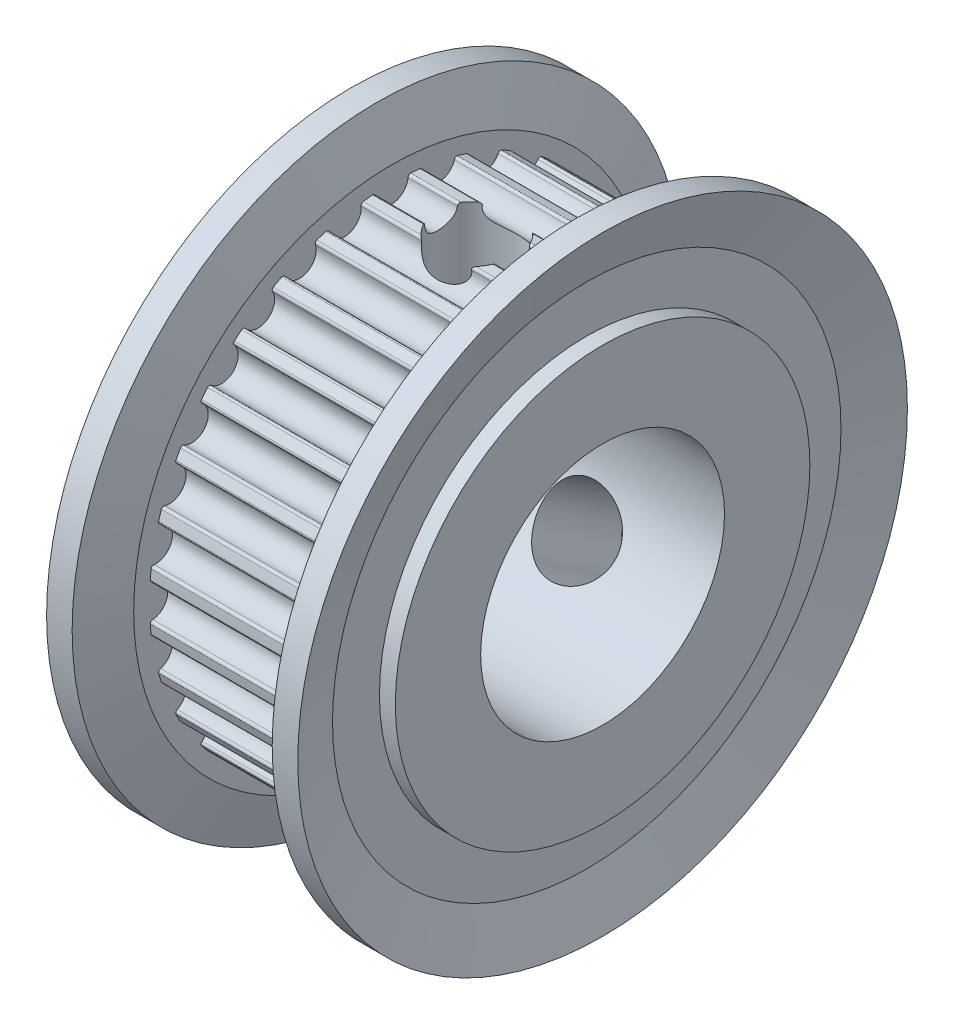
SolidWorks part; units mm, degrees
ref_plane "Front Plane" through (0, 0, 0) normal (0, 0, 1) x (1, 0, 0)
ref_plane "Top Plane" through (0, 0, 0) normal (0, 1, 0) x (1, 0, 0)
ref_plane "Right Plane" through (0, 0, 0) normal (1, 0, 0) x (0, 0, -1)
ref_plane "Plane1" through (0, 0, 0) normal (0, 0, 1) x (1, 0, 0)
sketch "Sketch1" plane through (0, 0, 0) normal (0, 0, 1) x (1, 0, 0)
  line L0 (-5.15, 0) -> (-5.15, 8.5)
  line L1 (-5.15, 8.5) -> (-3.5, 8.5)
  line L2 (-3.5, 8.5) -> (-3.5, 9.93)
  line L3 (-3.5, 9.93) -> (3.5, 9.93)
  line L4 (3.5, 9.93) -> (3.5, 8.5)
  line L5 (3.5, 8.5) -> (5.15, 8.5)
  line L6 (5.15, 8.5) -> (5.15, 0)
  line L7 (5.15, 0) -> (-5.15, 0)
  line L8 (5.15, 0) -> (-5.15, 0) construction
revolve "Revolve1" add sketch "Sketch1" angle 360 about L8
ref_plane "Plane2" through (0, 0, 0) normal (1, 0, 0) x (0, 0, -1)
sketch "Sketch2" plane through (0, 0, 0) normal (1, 0, 0) x (0, 0, -1)
  line L0 (-0.9509, 10.1405) -> (-0.9273, 9.8885)
  line L1 (-0.9273, 9.8885) -> (-0.793, 9.8993)
  line L2 (0.793, 9.8993) -> (0.9273, 9.8885)
  line L3 (0.9273, 9.8885) -> (0.9509, 10.1405)
  arc A0 (-0.793, 9.8993) -> (-0.6724, 9.7974) centre (-0.784, 9.7876) cw
  arc A1 (-0.6724, 9.7974) -> (0.6724, 9.7974) centre (0, 9.856) ccw
  arc A2 (0.6724, 9.7974) -> (0.793, 9.8993) centre (0.784, 9.7876) cw
  arc A3 (0.9509, 10.1405) -> (-0.9509, 10.1405) centre (0, 0) ccw
extrude "Cut-Extrude1" cut sketch "Sketch2" against normal blind 3.5 and the other way blind 3.5
ref_plane "Plane3" through (0, 0, 0) normal (1, 0, 0) x (0, 0, -1)
sketch "Sketch3" plane through (0, 0, 0) normal (1, 0, 0) x (0, 0, -1)
  line L0 (-2.911, 9.7602) -> (-2.8386, 9.5176)
  line L1 (-2.8386, 9.5176) -> (-2.709, 9.5544)
  line L2 (-1.1535, 9.8638) -> (-1.0197, 9.8794)
  line L3 (-1.0197, 9.8794) -> (-1.0457, 10.1312)
  arc A0 (-2.709, 9.5544) -> (-2.5709, 9.4779) centre (-2.6784, 9.4466) cw
  arc A1 (-2.5709, 9.4779) -> (-1.2518, 9.7403) centre (-1.9228, 9.6666) ccw
  arc A2 (-1.2518, 9.7403) -> (-1.1535, 9.8638) centre (-1.1405, 9.7525) cw
  arc A3 (-1.0457, 10.1312) -> (-2.911, 9.7602) centre (0, 0) ccw
extrude "Cut-Extrude2" cut sketch "Sketch3" against normal blind 3.5 and the other way blind 3.5
ref_plane "Plane4" through (0, 0, 0) normal (1, 0, 0) x (0, 0, -1)
sketch "Sketch4" plane through (0, 0, 0) normal (1, 0, 0) x (0, 0, -1)
  line L0 (-4.7591, 9.0047) -> (-4.6409, 8.781)
  line L1 (-4.6409, 8.781) -> (-4.5209, 8.8423)
  line L2 (-3.0557, 9.4492) -> (-2.9275, 9.4907)
  line L3 (-2.9275, 9.4907) -> (-3.0021, 9.7325)
  arc A0 (-4.5209, 8.8423) -> (-4.3706, 8.7943) centre (-4.4699, 8.7426) cw
  arc A1 (-4.3706, 8.7943) -> (-3.128, 9.3089) centre (-3.7717, 9.1058) ccw
  arc A2 (-3.128, 9.3089) -> (-3.0557, 9.4492) centre (-3.0212, 9.3426) cw
  arc A3 (-3.0021, 9.7325) -> (-4.7591, 9.0047) centre (0, 0) ccw
extrude "Cut-Extrude3" cut sketch "Sketch4" against normal blind 3.5 and the other way blind 3.5
ref_plane "Plane5" through (0, 0, 0) normal (1, 0, 0) x (0, 0, -1)
sketch "Sketch5" plane through (0, 0, 0) normal (1, 0, 0) x (0, 0, -1)
  line L0 (-6.4244, 7.9032) -> (-6.2648, 7.7068)
  line L1 (-6.2648, 7.7068) -> (-6.1591, 7.7904)
  line L2 (-4.8404, 8.6715) -> (-4.7228, 8.7372)
  line L3 (-4.7228, 8.7372) -> (-4.8431, 8.9598)
  arc A0 (-6.1591, 7.7904) -> (-6.0023, 7.7726) centre (-6.0896, 7.7026) cw
  arc A1 (-6.0023, 7.7726) -> (-4.884, 8.5198) centre (-5.4757, 8.195) ccw
  arc A2 (-4.884, 8.5198) -> (-4.8404, 8.6715) centre (-4.7858, 8.5737) cw
  arc A3 (-4.8431, 8.9598) -> (-6.4244, 7.9032) centre (0, 0) ccw
extrude "Cut-Extrude4" cut sketch "Sketch5" against normal blind 3.5 and the other way blind 3.5
ref_plane "Plane6" through (0, 0, 0) normal (1, 0, 0) x (0, 0, -1)
sketch "Sketch6" plane through (0, 0, 0) normal (1, 0, 0) x (0, 0, -1)
  line L0 (-7.8428, 6.498) -> (-7.6479, 6.3366)
  line L1 (-7.6479, 6.3366) -> (-7.5606, 6.4391)
  line L2 (-6.4391, 7.5606) -> (-6.3366, 7.6479)
  line L3 (-6.3366, 7.6479) -> (-6.498, 7.8428)
  arc A0 (-7.5606, 6.4391) -> (-7.4033, 6.4523) centre (-7.4753, 6.3665) cw
  arc A1 (-7.4033, 6.4523) -> (-6.4523, 7.4033) centre (-6.9692, 6.9692) ccw
  arc A2 (-6.4523, 7.4033) -> (-6.4391, 7.5606) centre (-6.3665, 7.4753) cw
  arc A3 (-6.498, 7.8428) -> (-7.8428, 6.498) centre (0, 0) ccw
extrude "Cut-Extrude5" cut sketch "Sketch6" against normal blind 3.5 and the other way blind 3.5
ref_plane "Plane7" through (0, 0, 0) normal (1, 0, 0) x (0, 0, -1)
sketch "Sketch7" plane through (0, 0, 0) normal (1, 0, 0) x (0, 0, -1)
  line L0 (-8.9598, 4.8431) -> (-8.7372, 4.7228)
  line L1 (-8.7372, 4.7228) -> (-8.6715, 4.8404)
  line L2 (-7.7904, 6.1591) -> (-7.7068, 6.2648)
  line L3 (-7.7068, 6.2648) -> (-7.9032, 6.4244)
  arc A0 (-8.6715, 4.8404) -> (-8.5198, 4.884) centre (-8.5737, 4.7858) cw
  arc A1 (-8.5198, 4.884) -> (-7.7726, 6.0023) centre (-8.195, 5.4757) ccw
  arc A2 (-7.7726, 6.0023) -> (-7.7904, 6.1591) centre (-7.7026, 6.0896) cw
  arc A3 (-7.9032, 6.4244) -> (-8.9598, 4.8431) centre (0, 0) ccw
extrude "Cut-Extrude6" cut sketch "Sketch7" against normal blind 3.5 and the other way blind 3.5
ref_plane "Plane8" through (0, 0, 0) normal (1, 0, 0) x (0, 0, -1)
sketch "Sketch8" plane through (0, 0, 0) normal (1, 0, 0) x (0, 0, -1)
  line L0 (-9.7325, 3.0021) -> (-9.4907, 2.9275)
  line L1 (-9.4907, 2.9275) -> (-9.4492, 3.0557)
  line L2 (-8.8423, 4.5209) -> (-8.781, 4.6409)
  line L3 (-8.781, 4.6409) -> (-9.0047, 4.7591)
  arc A0 (-9.4492, 3.0557) -> (-9.3089, 3.128) centre (-9.3426, 3.0212) cw
  arc A1 (-9.3089, 3.128) -> (-8.7943, 4.3706) centre (-9.1058, 3.7717) ccw
  arc A2 (-8.7943, 4.3706) -> (-8.8423, 4.5209) centre (-8.7426, 4.4699) cw
  arc A3 (-9.0047, 4.7591) -> (-9.7325, 3.0021) centre (0, 0) ccw
extrude "Cut-Extrude7" cut sketch "Sketch8" against normal blind 3.5 and the other way blind 3.5
ref_plane "Plane9" through (0, 0, 0) normal (1, 0, 0) x (0, 0, -1)
sketch "Sketch9" plane through (0, 0, 0) normal (1, 0, 0) x (0, 0, -1)
  line L0 (-10.1312, 1.0457) -> (-9.8794, 1.0197)
  line L1 (-9.8794, 1.0197) -> (-9.8638, 1.1535)
  line L2 (-9.5544, 2.709) -> (-9.5176, 2.8386)
  line L3 (-9.5176, 2.8386) -> (-9.7602, 2.911)
  arc A0 (-9.8638, 1.1535) -> (-9.7403, 1.2518) centre (-9.7525, 1.1405) cw
  arc A1 (-9.7403, 1.2518) -> (-9.4779, 2.5709) centre (-9.6666, 1.9228) ccw
  arc A2 (-9.4779, 2.5709) -> (-9.5544, 2.709) centre (-9.4466, 2.6784) cw
  arc A3 (-9.7602, 2.911) -> (-10.1312, 1.0457) centre (0, 0) ccw
extrude "Cut-Extrude8" cut sketch "Sketch9" against normal blind 3.5 and the other way blind 3.5
ref_plane "Plane10" through (0, 0, 0) normal (1, 0, 0) x (0, 0, -1)
sketch "Sketch10" plane through (0, 0, 0) normal (1, 0, 0) x (0, 0, -1)
  line L0 (-10.1405, -0.9509) -> (-9.8885, -0.9273)
  line L1 (-9.8885, -0.9273) -> (-9.8993, -0.793)
  line L2 (-9.8993, 0.793) -> (-9.8885, 0.9273)
  line L3 (-9.8885, 0.9273) -> (-10.1405, 0.9509)
  arc A0 (-9.8993, -0.793) -> (-9.7974, -0.6724) centre (-9.7876, -0.784) cw
  arc A1 (-9.7974, -0.6724) -> (-9.7974, 0.6724) centre (-9.856, 0) ccw
  arc A2 (-9.7974, 0.6724) -> (-9.8993, 0.793) centre (-9.7876, 0.784) cw
  arc A3 (-10.1405, 0.9509) -> (-10.1405, -0.9509) centre (0, 0) ccw
extrude "Cut-Extrude9" cut sketch "Sketch10" against normal blind 3.5 and the other way blind 3.5
ref_plane "Plane11" through (0, 0, 0) normal (1, 0, 0) x (0, 0, -1)
sketch "Sketch11" plane through (0, 0, 0) normal (1, 0, 0) x (0, 0, -1)
  line L0 (-9.7602, -2.911) -> (-9.5176, -2.8386)
  line L1 (-9.5176, -2.8386) -> (-9.5544, -2.709)
  line L2 (-9.8638, -1.1535) -> (-9.8794, -1.0197)
  line L3 (-9.8794, -1.0197) -> (-10.1312, -1.0457)
  arc A0 (-9.5544, -2.709) -> (-9.4779, -2.5709) centre (-9.4466, -2.6784) cw
  arc A1 (-9.4779, -2.5709) -> (-9.7403, -1.2518) centre (-9.6666, -1.9228) ccw
  arc A2 (-9.7403, -1.2518) -> (-9.8638, -1.1535) centre (-9.7525, -1.1405) cw
  arc A3 (-10.1312, -1.0457) -> (-9.7602, -2.911) centre (0, 0) ccw
extrude "Cut-Extrude10" cut sketch "Sketch11" against normal blind 3.5 and the other way blind 3.5
ref_plane "Plane12" through (0, 0, 0) normal (1, 0, 0) x (0, 0, -1)
sketch "Sketch12" plane through (0, 0, 0) normal (1, 0, 0) x (0, 0, -1)
  line L0 (-9.0047, -4.7591) -> (-8.781, -4.6409)
  line L1 (-8.781, -4.6409) -> (-8.8423, -4.5209)
  line L2 (-9.4492, -3.0557) -> (-9.4907, -2.9275)
  line L3 (-9.4907, -2.9275) -> (-9.7325, -3.0021)
  arc A0 (-8.8423, -4.5209) -> (-8.7943, -4.3706) centre (-8.7426, -4.4699) cw
  arc A1 (-8.7943, -4.3706) -> (-9.3089, -3.128) centre (-9.1058, -3.7717) ccw
  arc A2 (-9.3089, -3.128) -> (-9.4492, -3.0557) centre (-9.3426, -3.0212) cw
  arc A3 (-9.7325, -3.0021) -> (-9.0047, -4.7591) centre (0, 0) ccw
extrude "Cut-Extrude11" cut sketch "Sketch12" against normal blind 3.5 and the other way blind 3.5
ref_plane "Plane13" through (0, 0, 0) normal (1, 0, 0) x (0, 0, -1)
sketch "Sketch13" plane through (0, 0, 0) normal (1, 0, 0) x (0, 0, -1)
  line L0 (-7.9032, -6.4244) -> (-7.7068, -6.2648)
  line L1 (-7.7068, -6.2648) -> (-7.7904, -6.1591)
  line L2 (-8.6715, -4.8404) -> (-8.7372, -4.7228)
  line L3 (-8.7372, -4.7228) -> (-8.9598, -4.8431)
  arc A0 (-7.7904, -6.1591) -> (-7.7726, -6.0023) centre (-7.7026, -6.0896) cw
  arc A1 (-7.7726, -6.0023) -> (-8.5198, -4.884) centre (-8.195, -5.4757) ccw
  arc A2 (-8.5198, -4.884) -> (-8.6715, -4.8404) centre (-8.5737, -4.7858) cw
  arc A3 (-8.9598, -4.8431) -> (-7.9032, -6.4244) centre (0, 0) ccw
extrude "Cut-Extrude12" cut sketch "Sketch13" against normal blind 3.5 and the other way blind 3.5
ref_plane "Plane14" through (0, 0, 0) normal (1, 0, 0) x (0, 0, -1)
sketch "Sketch14" plane through (0, 0, 0) normal (1, 0, 0) x (0, 0, -1)
  line L0 (-6.498, -7.8428) -> (-6.3366, -7.6479)
  line L1 (-6.3366, -7.6479) -> (-6.4391, -7.5606)
  line L2 (-7.5606, -6.4391) -> (-7.6479, -6.3366)
  line L3 (-7.6479, -6.3366) -> (-7.8428, -6.498)
  arc A0 (-6.4391, -7.5606) -> (-6.4523, -7.4033) centre (-6.3665, -7.4753) cw
  arc A1 (-6.4523, -7.4033) -> (-7.4033, -6.4523) centre (-6.9692, -6.9692) ccw
  arc A2 (-7.4033, -6.4523) -> (-7.5606, -6.4391) centre (-7.4753, -6.3665) cw
  arc A3 (-7.8428, -6.498) -> (-6.498, -7.8428) centre (0, 0) ccw
extrude "Cut-Extrude13" cut sketch "Sketch14" against normal blind 3.5 and the other way blind 3.5
ref_plane "Plane15" through (0, 0, 0) normal (1, 0, 0) x (0, 0, -1)
sketch "Sketch15" plane through (0, 0, 0) normal (1, 0, 0) x (0, 0, -1)
  line L0 (-4.8431, -8.9598) -> (-4.7228, -8.7372)
  line L1 (-4.7228, -8.7372) -> (-4.8404, -8.6715)
  line L2 (-6.1591, -7.7904) -> (-6.2648, -7.7068)
  line L3 (-6.2648, -7.7068) -> (-6.4244, -7.9032)
  arc A0 (-4.8404, -8.6715) -> (-4.884, -8.5198) centre (-4.7858, -8.5737) cw
  arc A1 (-4.884, -8.5198) -> (-6.0023, -7.7726) centre (-5.4757, -8.195) ccw
  arc A2 (-6.0023, -7.7726) -> (-6.1591, -7.7904) centre (-6.0896, -7.7026) cw
  arc A3 (-6.4244, -7.9032) -> (-4.8431, -8.9598) centre (0, 0) ccw
extrude "Cut-Extrude14" cut sketch "Sketch15" against normal blind 3.5 and the other way blind 3.5
ref_plane "Plane16" through (0, 0, 0) normal (1, 0, 0) x (0, 0, -1)
sketch "Sketch16" plane through (0, 0, 0) normal (1, 0, 0) x (0, 0, -1)
  line L0 (-3.0021, -9.7325) -> (-2.9275, -9.4907)
  line L1 (-2.9275, -9.4907) -> (-3.0557, -9.4492)
  line L2 (-4.5209, -8.8423) -> (-4.6409, -8.781)
  line L3 (-4.6409, -8.781) -> (-4.7591, -9.0047)
  arc A0 (-3.0557, -9.4492) -> (-3.128, -9.3089) centre (-3.0212, -9.3426) cw
  arc A1 (-3.128, -9.3089) -> (-4.3706, -8.7943) centre (-3.7717, -9.1058) ccw
  arc A2 (-4.3706, -8.7943) -> (-4.5209, -8.8423) centre (-4.4699, -8.7426) cw
  arc A3 (-4.7591, -9.0047) -> (-3.0021, -9.7325) centre (0, 0) ccw
extrude "Cut-Extrude15" cut sketch "Sketch16" against normal blind 3.5 and the other way blind 3.5
ref_plane "Plane17" through (0, 0, 0) normal (1, 0, 0) x (0, 0, -1)
sketch "Sketch17" plane through (0, 0, 0) normal (1, 0, 0) x (0, 0, -1)
  line L0 (-1.0457, -10.1312) -> (-1.0197, -9.8794)
  line L1 (-1.0197, -9.8794) -> (-1.1535, -9.8638)
  line L2 (-2.709, -9.5544) -> (-2.8386, -9.5176)
  line L3 (-2.8386, -9.5176) -> (-2.911, -9.7602)
  arc A0 (-1.1535, -9.8638) -> (-1.2518, -9.7403) centre (-1.1405, -9.7525) cw
  arc A1 (-1.2518, -9.7403) -> (-2.5709, -9.4779) centre (-1.9228, -9.6666) ccw
  arc A2 (-2.5709, -9.4779) -> (-2.709, -9.5544) centre (-2.6784, -9.4466) cw
  arc A3 (-2.911, -9.7602) -> (-1.0457, -10.1312) centre (0, 0) ccw
extrude "Cut-Extrude16" cut sketch "Sketch17" against normal blind 3.5 and the other way blind 3.5
ref_plane "Plane18" through (0, 0, 0) normal (1, 0, 0) x (0, 0, -1)
sketch "Sketch18" plane through (0, 0, 0) normal (1, 0, 0) x (0, 0, -1)
  line L0 (0.9509, -10.1405) -> (0.9273, -9.8885)
  line L1 (0.9273, -9.8885) -> (0.793, -9.8993)
  line L2 (-0.793, -9.8993) -> (-0.9273, -9.8885)
  line L3 (-0.9273, -9.8885) -> (-0.9509, -10.1405)
  arc A0 (0.793, -9.8993) -> (0.6724, -9.7974) centre (0.784, -9.7876) cw
  arc A1 (0.6724, -9.7974) -> (-0.6724, -9.7974) centre (0, -9.856) ccw
  arc A2 (-0.6724, -9.7974) -> (-0.793, -9.8993) centre (-0.784, -9.7876) cw
  arc A3 (-0.9509, -10.1405) -> (0.9509, -10.1405) centre (0, 0) ccw
extrude "Cut-Extrude17" cut sketch "Sketch18" against normal blind 3.5 and the other way blind 3.5
ref_plane "Plane19" through (0, 0, 0) normal (1, 0, 0) x (0, 0, -1)
sketch "Sketch19" plane through (0, 0, 0) normal (1, 0, 0) x (0, 0, -1)
  line L0 (2.911, -9.7602) -> (2.8386, -9.5176)
  line L1 (2.8386, -9.5176) -> (2.709, -9.5544)
  line L2 (1.1535, -9.8638) -> (1.0197, -9.8794)
  line L3 (1.0197, -9.8794) -> (1.0457, -10.1312)
  arc A0 (2.709, -9.5544) -> (2.5709, -9.4779) centre (2.6784, -9.4466) cw
  arc A1 (2.5709, -9.4779) -> (1.2518, -9.7403) centre (1.9228, -9.6666) ccw
  arc A2 (1.2518, -9.7403) -> (1.1535, -9.8638) centre (1.1405, -9.7525) cw
  arc A3 (1.0457, -10.1312) -> (2.911, -9.7602) centre (0, 0) ccw
extrude "Cut-Extrude18" cut sketch "Sketch19" against normal blind 3.5 and the other way blind 3.5
ref_plane "Plane20" through (0, 0, 0) normal (1, 0, 0) x (0, 0, -1)
sketch "Sketch20" plane through (0, 0, 0) normal (1, 0, 0) x (0, 0, -1)
  line L0 (4.7591, -9.0047) -> (4.6409, -8.781)
  line L1 (4.6409, -8.781) -> (4.5209, -8.8423)
  line L2 (3.0557, -9.4492) -> (2.9275, -9.4907)
  line L3 (2.9275, -9.4907) -> (3.0021, -9.7325)
  arc A0 (4.5209, -8.8423) -> (4.3706, -8.7943) centre (4.4699, -8.7426) cw
  arc A1 (4.3706, -8.7943) -> (3.128, -9.3089) centre (3.7717, -9.1058) ccw
  arc A2 (3.128, -9.3089) -> (3.0557, -9.4492) centre (3.0212, -9.3426) cw
  arc A3 (3.0021, -9.7325) -> (4.7591, -9.0047) centre (0, 0) ccw
extrude "Cut-Extrude19" cut sketch "Sketch20" against normal blind 3.5 and the other way blind 3.5
ref_plane "Plane21" through (0, 0, 0) normal (1, 0, 0) x (0, 0, -1)
sketch "Sketch21" plane through (0, 0, 0) normal (1, 0, 0) x (0, 0, -1)
  line L0 (6.4244, -7.9032) -> (6.2648, -7.7068)
  line L1 (6.2648, -7.7068) -> (6.1591, -7.7904)
  line L2 (4.8404, -8.6715) -> (4.7228, -8.7372)
  line L3 (4.7228, -8.7372) -> (4.8431, -8.9598)
  arc A0 (6.1591, -7.7904) -> (6.0023, -7.7726) centre (6.0896, -7.7026) cw
  arc A1 (6.0023, -7.7726) -> (4.884, -8.5198) centre (5.4757, -8.195) ccw
  arc A2 (4.884, -8.5198) -> (4.8404, -8.6715) centre (4.7858, -8.5737) cw
  arc A3 (4.8431, -8.9598) -> (6.4244, -7.9032) centre (0, 0) ccw
extrude "Cut-Extrude20" cut sketch "Sketch21" against normal blind 3.5 and the other way blind 3.5
ref_plane "Plane22" through (0, 0, 0) normal (1, 0, 0) x (0, 0, -1)
sketch "Sketch22" plane through (0, 0, 0) normal (1, 0, 0) x (0, 0, -1)
  line L0 (7.8428, -6.498) -> (7.6479, -6.3366)
  line L1 (7.6479, -6.3366) -> (7.5606, -6.4391)
  line L2 (6.4391, -7.5606) -> (6.3366, -7.6479)
  line L3 (6.3366, -7.6479) -> (6.498, -7.8428)
  arc A0 (7.5606, -6.4391) -> (7.4033, -6.4523) centre (7.4753, -6.3665) cw
  arc A1 (7.4033, -6.4523) -> (6.4523, -7.4033) centre (6.9692, -6.9692) ccw
  arc A2 (6.4523, -7.4033) -> (6.4391, -7.5606) centre (6.3665, -7.4753) cw
  arc A3 (6.498, -7.8428) -> (7.8428, -6.498) centre (0, 0) ccw
extrude "Cut-Extrude21" cut sketch "Sketch22" against normal blind 3.5 and the other way blind 3.5
ref_plane "Plane23" through (0, 0, 0) normal (1, 0, 0) x (0, 0, -1)
sketch "Sketch23" plane through (0, 0, 0) normal (1, 0, 0) x (0, 0, -1)
  line L0 (8.9598, -4.8431) -> (8.7372, -4.7228)
  line L1 (8.7372, -4.7228) -> (8.6715, -4.8404)
  line L2 (7.7904, -6.1591) -> (7.7068, -6.2648)
  line L3 (7.7068, -6.2648) -> (7.9032, -6.4244)
  arc A0 (8.6715, -4.8404) -> (8.5198, -4.884) centre (8.5737, -4.7858) cw
  arc A1 (8.5198, -4.884) -> (7.7726, -6.0023) centre (8.195, -5.4757) ccw
  arc A2 (7.7726, -6.0023) -> (7.7904, -6.1591) centre (7.7026, -6.0896) cw
  arc A3 (7.9032, -6.4244) -> (8.9598, -4.8431) centre (0, 0) ccw
extrude "Cut-Extrude22" cut sketch "Sketch23" against normal blind 3.5 and the other way blind 3.5
ref_plane "Plane24" through (0, 0, 0) normal (1, 0, 0) x (0, 0, -1)
sketch "Sketch24" plane through (0, 0, 0) normal (1, 0, 0) x (0, 0, -1)
  line L0 (9.7325, -3.0021) -> (9.4907, -2.9275)
  line L1 (9.4907, -2.9275) -> (9.4492, -3.0557)
  line L2 (8.8423, -4.5209) -> (8.781, -4.6409)
  line L3 (8.781, -4.6409) -> (9.0047, -4.7591)
  arc A0 (9.4492, -3.0557) -> (9.3089, -3.128) centre (9.3426, -3.0212) cw
  arc A1 (9.3089, -3.128) -> (8.7943, -4.3706) centre (9.1058, -3.7717) ccw
  arc A2 (8.7943, -4.3706) -> (8.8423, -4.5209) centre (8.7426, -4.4699) cw
  arc A3 (9.0047, -4.7591) -> (9.7325, -3.0021) centre (0, 0) ccw
extrude "Cut-Extrude23" cut sketch "Sketch24" against normal blind 3.5 and the other way blind 3.5
ref_plane "Plane25" through (0, 0, 0) normal (1, 0, 0) x (0, 0, -1)
sketch "Sketch25" plane through (0, 0, 0) normal (1, 0, 0) x (0, 0, -1)
  line L0 (10.1312, -1.0457) -> (9.8794, -1.0197)
  line L1 (9.8794, -1.0197) -> (9.8638, -1.1535)
  line L2 (9.5544, -2.709) -> (9.5176, -2.8386)
  line L3 (9.5176, -2.8386) -> (9.7602, -2.911)
  arc A0 (9.8638, -1.1535) -> (9.7403, -1.2518) centre (9.7525, -1.1405) cw
  arc A1 (9.7403, -1.2518) -> (9.4779, -2.5709) centre (9.6666, -1.9228) ccw
  arc A2 (9.4779, -2.5709) -> (9.5544, -2.709) centre (9.4466, -2.6784) cw
  arc A3 (9.7602, -2.911) -> (10.1312, -1.0457) centre (0, 0) ccw
extrude "Cut-Extrude24" cut sketch "Sketch25" against normal blind 3.5 and the other way blind 3.5
ref_plane "Plane26" through (0, 0, 0) normal (1, 0, 0) x (0, 0, -1)
sketch "Sketch26" plane through (0, 0, 0) normal (1, 0, 0) x (0, 0, -1)
  line L0 (10.1405, 0.9509) -> (9.8885, 0.9273)
  line L1 (9.8885, 0.9273) -> (9.8993, 0.793)
  line L2 (9.8993, -0.793) -> (9.8885, -0.9273)
  line L3 (9.8885, -0.9273) -> (10.1405, -0.9509)
  arc A0 (9.8993, 0.793) -> (9.7974, 0.6724) centre (9.7876, 0.784) cw
  arc A1 (9.7974, 0.6724) -> (9.7974, -0.6724) centre (9.856, 0) ccw
  arc A2 (9.7974, -0.6724) -> (9.8993, -0.793) centre (9.7876, -0.784) cw
  arc A3 (10.1405, -0.9509) -> (10.1405, 0.9509) centre (0, 0) ccw
extrude "Cut-Extrude25" cut sketch "Sketch26" against normal blind 3.5 and the other way blind 3.5
ref_plane "Plane27" through (0, 0, 0) normal (1, 0, 0) x (0, 0, -1)
sketch "Sketch27" plane through (0, 0, 0) normal (1, 0, 0) x (0, 0, -1)
  line L0 (9.7602, 2.911) -> (9.5176, 2.8386)
  line L1 (9.5176, 2.8386) -> (9.5544, 2.709)
  line L2 (9.8638, 1.1535) -> (9.8794, 1.0197)
  line L3 (9.8794, 1.0197) -> (10.1312, 1.0457)
  arc A0 (9.5544, 2.709) -> (9.4779, 2.5709) centre (9.4466, 2.6784) cw
  arc A1 (9.4779, 2.5709) -> (9.7403, 1.2518) centre (9.6666, 1.9228) ccw
  arc A2 (9.7403, 1.2518) -> (9.8638, 1.1535) centre (9.7525, 1.1405) cw
  arc A3 (10.1312, 1.0457) -> (9.7602, 2.911) centre (0, 0) ccw
extrude "Cut-Extrude26" cut sketch "Sketch27" against normal blind 3.5 and the other way blind 3.5
ref_plane "Plane28" through (0, 0, 0) normal (1, 0, 0) x (0, 0, -1)
sketch "Sketch28" plane through (0, 0, 0) normal (1, 0, 0) x (0, 0, -1)
  line L0 (9.0047, 4.7591) -> (8.781, 4.6409)
  line L1 (8.781, 4.6409) -> (8.8423, 4.5209)
  line L2 (9.4492, 3.0557) -> (9.4907, 2.9275)
  line L3 (9.4907, 2.9275) -> (9.7325, 3.0021)
  arc A0 (8.8423, 4.5209) -> (8.7943, 4.3706) centre (8.7426, 4.4699) cw
  arc A1 (8.7943, 4.3706) -> (9.3089, 3.128) centre (9.1058, 3.7717) ccw
  arc A2 (9.3089, 3.128) -> (9.4492, 3.0557) centre (9.3426, 3.0212) cw
  arc A3 (9.7325, 3.0021) -> (9.0047, 4.7591) centre (0, 0) ccw
extrude "Cut-Extrude27" cut sketch "Sketch28" against normal blind 3.5 and the other way blind 3.5
ref_plane "Plane29" through (0, 0, 0) normal (1, 0, 0) x (0, 0, -1)
sketch "Sketch29" plane through (0, 0, 0) normal (1, 0, 0) x (0, 0, -1)
  line L0 (7.9032, 6.4244) -> (7.7068, 6.2648)
  line L1 (7.7068, 6.2648) -> (7.7904, 6.1591)
  line L2 (8.6715, 4.8404) -> (8.7372, 4.7228)
  line L3 (8.7372, 4.7228) -> (8.9598, 4.8431)
  arc A0 (7.7904, 6.1591) -> (7.7726, 6.0023) centre (7.7026, 6.0896) cw
  arc A1 (7.7726, 6.0023) -> (8.5198, 4.884) centre (8.195, 5.4757) ccw
  arc A2 (8.5198, 4.884) -> (8.6715, 4.8404) centre (8.5737, 4.7858) cw
  arc A3 (8.9598, 4.8431) -> (7.9032, 6.4244) centre (0, 0) ccw
extrude "Cut-Extrude28" cut sketch "Sketch29" against normal blind 3.5 and the other way blind 3.5
ref_plane "Plane30" through (0, 0, 0) normal (1, 0, 0) x (0, 0, -1)
sketch "Sketch30" plane through (0, 0, 0) normal (1, 0, 0) x (0, 0, -1)
  line L0 (6.498, 7.8428) -> (6.3366, 7.6479)
  line L1 (6.3366, 7.6479) -> (6.4391, 7.5606)
  line L2 (7.5606, 6.4391) -> (7.6479, 6.3366)
  line L3 (7.6479, 6.3366) -> (7.8428, 6.498)
  arc A0 (6.4391, 7.5606) -> (6.4523, 7.4033) centre (6.3665, 7.4753) cw
  arc A1 (6.4523, 7.4033) -> (7.4033, 6.4523) centre (6.9692, 6.9692) ccw
  arc A2 (7.4033, 6.4523) -> (7.5606, 6.4391) centre (7.4753, 6.3665) cw
  arc A3 (7.8428, 6.498) -> (6.498, 7.8428) centre (0, 0) ccw
extrude "Cut-Extrude29" cut sketch "Sketch30" against normal blind 3.5 and the other way blind 3.5
ref_plane "Plane31" through (0, 0, 0) normal (1, 0, 0) x (0, 0, -1)
sketch "Sketch31" plane through (0, 0, 0) normal (1, 0, 0) x (0, 0, -1)
  line L0 (4.8431, 8.9598) -> (4.7228, 8.7372)
  line L1 (4.7228, 8.7372) -> (4.8404, 8.6715)
  line L2 (6.1591, 7.7904) -> (6.2648, 7.7068)
  line L3 (6.2648, 7.7068) -> (6.4244, 7.9032)
  arc A0 (4.8404, 8.6715) -> (4.884, 8.5198) centre (4.7858, 8.5737) cw
  arc A1 (4.884, 8.5198) -> (6.0023, 7.7726) centre (5.4757, 8.195) ccw
  arc A2 (6.0023, 7.7726) -> (6.1591, 7.7904) centre (6.0896, 7.7026) cw
  arc A3 (6.4244, 7.9032) -> (4.8431, 8.9598) centre (0, 0) ccw
extrude "Cut-Extrude30" cut sketch "Sketch31" against normal blind 3.5 and the other way blind 3.5
ref_plane "Plane32" through (0, 0, 0) normal (1, 0, 0) x (0, 0, -1)
sketch "Sketch32" plane through (0, 0, 0) normal (1, 0, 0) x (0, 0, -1)
  line L0 (3.0021, 9.7325) -> (2.9275, 9.4907)
  line L1 (2.9275, 9.4907) -> (3.0557, 9.4492)
  line L2 (4.5209, 8.8423) -> (4.6409, 8.781)
  line L3 (4.6409, 8.781) -> (4.7591, 9.0047)
  arc A0 (3.0557, 9.4492) -> (3.128, 9.3089) centre (3.0212, 9.3426) cw
  arc A1 (3.128, 9.3089) -> (4.3706, 8.7943) centre (3.7717, 9.1058) ccw
  arc A2 (4.3706, 8.7943) -> (4.5209, 8.8423) centre (4.4699, 8.7426) cw
  arc A3 (4.7591, 9.0047) -> (3.0021, 9.7325) centre (0, 0) ccw
extrude "Cut-Extrude31" cut sketch "Sketch32" against normal blind 3.5 and the other way blind 3.5
ref_plane "Plane33" through (0, 0, 0) normal (1, 0, 0) x (0, 0, -1)
sketch "Sketch33" plane through (0, 0, 0) normal (1, 0, 0) x (0, 0, -1)
  line L0 (1.0457, 10.1312) -> (1.0197, 9.8794)
  line L1 (1.0197, 9.8794) -> (1.1535, 9.8638)
  line L2 (2.709, 9.5544) -> (2.8386, 9.5176)
  line L3 (2.8386, 9.5176) -> (2.911, 9.7602)
  arc A0 (1.1535, 9.8638) -> (1.2518, 9.7403) centre (1.1405, 9.7525) cw
  arc A1 (1.2518, 9.7403) -> (2.5709, 9.4779) centre (1.9228, 9.6666) ccw
  arc A2 (2.5709, 9.4779) -> (2.709, 9.5544) centre (2.6784, 9.4466) cw
  arc A3 (2.911, 9.7602) -> (1.0457, 10.1312) centre (0, 0) ccw
extrude "Cut-Extrude32" cut sketch "Sketch33" against normal blind 3.5 and the other way blind 3.5
ref_plane "Plane34" through (0, 0, 0) normal (0, 0, 1) x (1, 0, 0)
sketch "Sketch34" plane through (0, 0, 0) normal (0, 0, 1) x (1, 0, 0)
  line L0 (3.5, 8.5) -> (4.5, 8.5)
  line L1 (4.5, 8.5) -> (4.5, 10.425)
  line L2 (4.5, 10.425) -> (5.15, 12.5)
  line L3 (5.15, 12.5) -> (4.1021, 12.5)
  line L4 (4.1021, 12.5) -> (3.5, 10.578)
  line L5 (3.5, 10.578) -> (3.5, 8.5)
  line L6 (50, 0) -> (-50, 0) construction
revolve "Revolve2" add sketch "Sketch34" angle 360 about L6
ref_plane "Plane35" through (0, 0, 0) normal (0, 0, 1) x (1, 0, 0)
sketch "Sketch35" plane through (0, 0, 0) normal (0, 0, 1) x (1, 0, 0)
  line L0 (-5.15, 12.5) -> (-4.5, 10.425)
  line L1 (-4.5, 10.425) -> (-4.5, 8.5)
  line L2 (-4.5, 8.5) -> (-3.5, 8.5)
  line L3 (-3.5, 8.5) -> (-3.5, 10.578)
  line L4 (-3.5, 10.578) -> (-4.1021, 12.5)
  line L5 (-4.1021, 12.5) -> (-5.15, 12.5)
  line L6 (50, 0) -> (-50, 0) construction
revolve "Revolve3" add sketch "Sketch35" angle 360 about L6
ref_plane "Plane36" through (0, 0, 0) normal (0, 0, 1) x (1, 0, 0)
sketch "Sketch36" plane through (0, 0, 0) normal (0, 0, 1) x (1, 0, 0)
  line L0 (-5.15, 0) -> (-5.15, 5)
  line L1 (-5.15, 5) -> (5.15, 5)
  line L2 (5.15, 5) -> (5.15, 0)
  line L3 (5.15, 0) -> (-5.15, 0)
  line L4 (5.15, 0) -> (-5.15, 0) construction
revolve "Cut-Revolve1" cut sketch "Sketch36" angle 360 about L4
ref_plane "Plane37" through (0, 0, 0) normal (1, 0, 0) x (0, 0, -1)
sketch "Sketch37" plane through (0, 0, 0) normal (1, 0, 0) x (0, 0, -1)
  line L0 (0, 9.93) -> (1.621, 9.93)
  line L1 (1.621, 9.93) -> (1.621, 0)
  line L2 (1.621, 0) -> (0, 0)
  line L3 (0, 0) -> (0, 9.93)
  line L4 (0, 0) -> (0, 9.93) construction
revolve "Cut-Revolve2" cut sketch "Sketch37" angle 360 about L4
ref_plane "Plane38" through (0, 0, 0) normal (1, 0, 0) x (0, 0, -1)
sketch "Sketch38" plane through (0, 0, 0) normal (1, 0, 0) x (0, 0, -1)
  line L0 (8.2565, -5.5168) -> (7.3559, -6.8646)
  line L1 (7.3559, -6.8646) -> (-0.9006, -1.3478)
  line L2 (-0.9006, -1.3478) -> (0, 0)
  line L3 (0, 0) -> (8.2565, -5.5168)
  line L4 (0, 0) -> (8.2565, -5.5168) construction
revolve "Cut-Revolve3" cut sketch "Sketch38" angle 360 about L4
